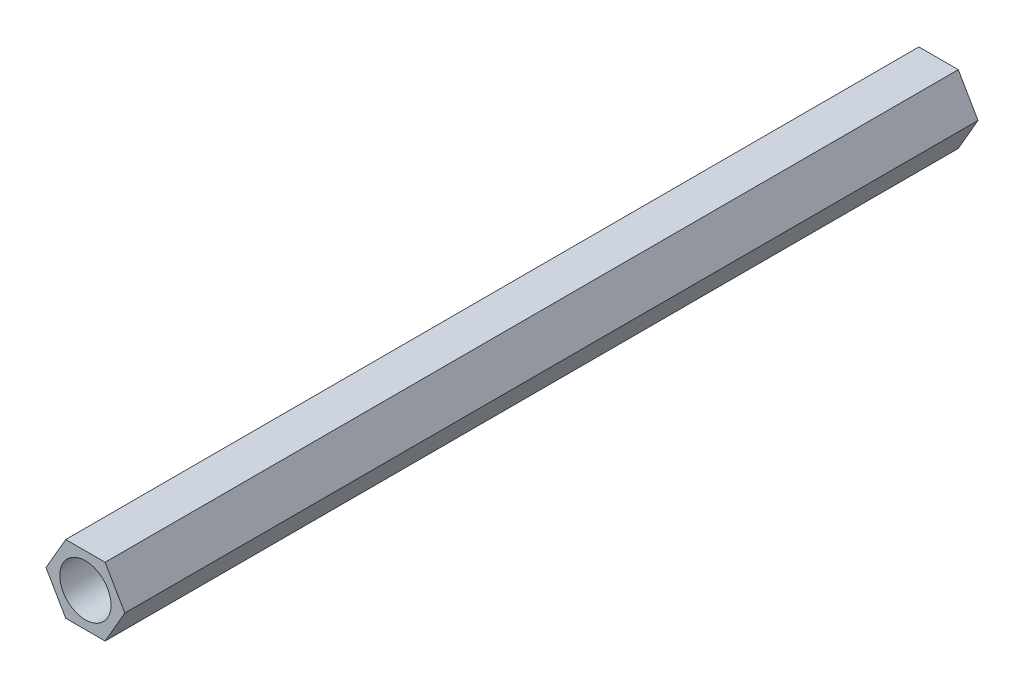
SolidWorks part; units mm, degrees
ref_plane "前视基准面" through (0, 0, 0) normal (0, 0, 1) x (1, 0, 0)
ref_plane "上视基准面" through (0, 0, 0) normal (0, 1, 0) x (1, 0, 0)
ref_plane "右视基准面" through (0, 0, 0) normal (1, 0, 0) x (0, 0, -1)
sketch "草图1" plane through (0, 0, 0) normal (0, 0, 1) x (1, 0, 0)
  line L1 (1.1547, -2) -> (2.3094, 0)
  line L2 (2.3094, 0) -> (1.1547, 2)
  line L3 (1.1547, 2) -> (-1.1547, 2)
  line L4 (-1.1547, 2) -> (-2.3094, 0)
  line L5 (-2.3094, 0) -> (-1.1547, -2)
  line L6 (-1.1547, -2) -> (1.1547, -2)
  circle A0 centre (0, 0) radius 2 construction
  circle A1 centre (0, 0) radius 1.5
  dimension "D1" = 3
  dimension "D2" = 2
extrude "凸台-拉伸1" add sketch "草图1" along normal blind 50
